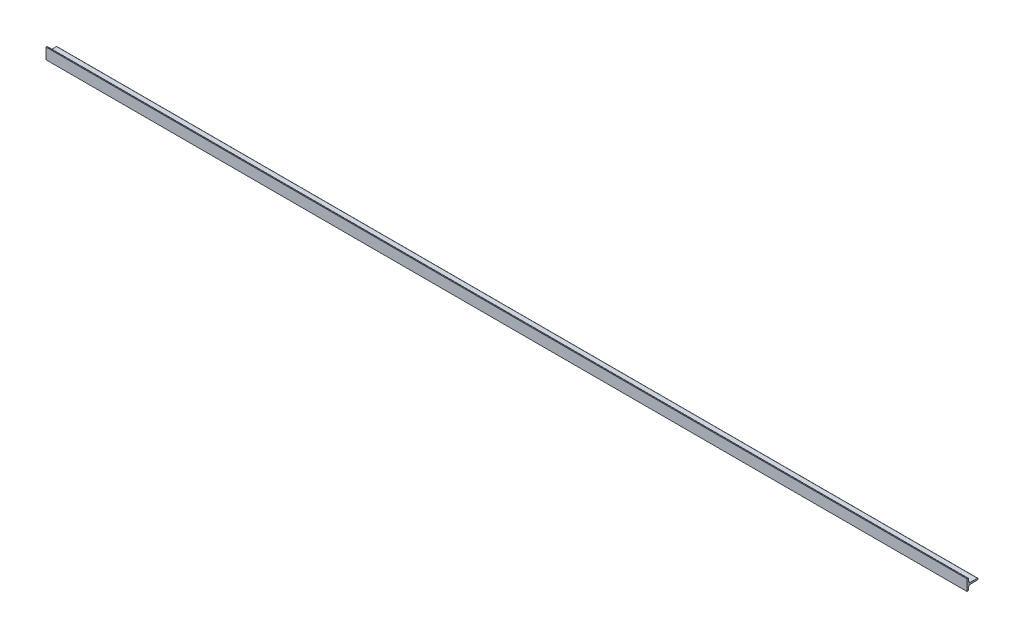
SolidWorks part; units mm, degrees
ref_plane "Front Plane" through (0, 0, 0) normal (0, 0, 1) x (1, 0, 0)
ref_plane "Top Plane" through (0, 0, 0) normal (0, 1, 0) x (1, 0, 0)
ref_plane "Right Plane" through (0, 0, 0) normal (1, 0, 0) x (0, 0, -1)
sketch "Sketch1" plane through (0, 0, 0) normal (0, 0, 1) x (1, 0, 0)
  line L0 (0, 0) -> (1674, 0)
  point P4 (0, 0)
  dimension "D1" = 1674
other "T section T 20 X 20(1)"
ref_plane "Plane1" through (0, 0, 0) normal (1, 0, 0) x (0, 1, 0)
sketch "Sketch12" plane through (0, 0, 0) normal (1, 0, 0) x (0, 1, 0)
  line L0 (-10, 20) -> (10, 20)
  line L2 (-1.3196, 0.98) -> (-1.581, 14.051)
  line L3 (-4.5204, 16.9904) -> (-8.53, 17.0706)
  line L5 (-10, 20) -> (-10, 18.5703)
  line L6 (10, 20) -> (10, 18.5703)
  line L7 (8.53, 17.0706) -> (4.5204, 16.9904)
  line L8 (1.581, 14.051) -> (1.3196, 0.98)
  line L9 (-5, 17) -> (5, 17) construction
  line L10 (0, 20) -> (0, 0) construction
  line L12 (-0.3198, 0) -> (0.3198, 0)
  arc A0 (-8.53, 17.0706) -> (-10, 18.5703) centre (-8.5, 18.5703) cw
  arc A1 (8.53, 17.0706) -> (10, 18.5703) centre (8.5, 18.5703) ccw
  arc A2 (-1.581, 14.051) -> (-4.5204, 16.9904) centre (-4.5804, 13.991) ccw
  arc A3 (4.5204, 16.9904) -> (1.581, 14.051) centre (4.5804, 13.991) ccw
  arc A4 (-0.3198, 0) -> (-1.3196, 0.98) centre (-0.3198, 1) cw
  arc A5 (1.3196, 0.98) -> (0.3198, 0) centre (0.3198, 1) cw
  point P16 (10, 17.1)
  point P24 (-1.3, 0)
  point P27 (1.3, 0)
  point P28 (0, 0)
  dimension "D2" = 1.146
  dimension "R2" = 1.5
  dimension "R1" = 3
  dimension "R3" = 1
  dimension "D1" = 1.146
  dimension "D3" = 2.9
  dimension "BF" = 20
  dimension "DEPTH" = 20
  dimension "TF" = 3
  dimension "D4" = 2.5999
  dimension "D5" = 1.146
